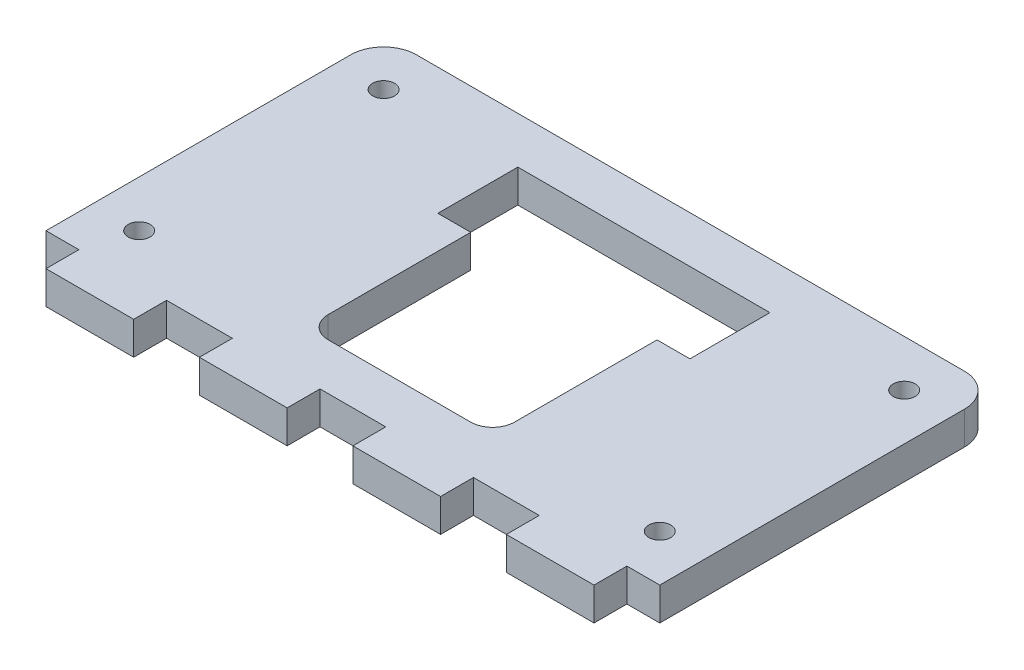
SolidWorks part; units mm, degrees
ref_plane "Plan de face" through (0, 0, 0) normal (0, 0, 1) x (1, 0, 0)
ref_plane "Plan de dessus" through (0, 0, 0) normal (0, 1, 0) x (1, 0, 0)
ref_plane "Plan de droite" through (0, 0, 0) normal (1, 0, 0) x (0, 0, -1)
sketch "Esquisse1" plane through (0, 0, 0) normal (0, 1, 0) x (1, 0, 0)
  line L0 (-28, -30.8) -> (-25, -30.8)
  line L1 (-25, 0) -> (25, 0)
  line L2 (-28, -3) -> (-28, -30.8)
  line L3 (-25, -33.8) -> (-17, -33.8)
  line L4 (28, -3) -> (28, -30.8)
  line L5 (-25, -30.8) -> (-25, -33.8)
  line L6 (-17, -33.8) -> (-17, -30.8)
  line L7 (-17, -30.8) -> (-11, -30.8)
  line L8 (-11, -30.8) -> (-11, -33.8)
  line L9 (-3, -33.8) -> (-3, -30.8)
  line L10 (-3, -30.8) -> (3, -30.8)
  line L11 (3, -30.8) -> (3, -33.8)
  line L12 (11, -33.8) -> (11, -30.8)
  line L13 (11, -30.8) -> (17, -30.8)
  line L14 (17, -30.8) -> (17, -33.8)
  line L15 (25, -33.8) -> (25, -30.8)
  line L16 (25, -30.8) -> (28, -30.8)
  line L17 (-11, -33.8) -> (-3, -33.8)
  line L18 (3, -33.8) -> (11, -33.8)
  line L19 (17, -33.8) -> (25, -33.8)
  line L20 (0, 0) -> (0, -30.8) construction
  line L21 (-11.5, -11.55) -> (-8.5, -11.55)
  line L22 (-23.75, -4.25) -> (23.75, -4.25) construction
  line L23 (-23.75, -4.25) -> (-23.75, -26.55) construction
  line L25 (23.75, -4.25) -> (23.75, -26.55) construction
  line L26 (-6.5, -26.55) -> (6.5, -26.55)
  line L27 (-11.5, -11.55) -> (-11.5, -4.25)
  line L28 (-11.5, -4.25) -> (11.5, -4.25)
  line L29 (11.5, -11.55) -> (11.5, -4.25)
  line L30 (-8.5, -11.55) -> (-8.5, -24.55)
  line L31 (11.5, -11.55) -> (8.5, -11.55)
  line L32 (8.5, -11.55) -> (8.5, -24.55)
  line L33 (-8.5, -26.55) -> (8.5, -26.55) construction
  line L34 (-23.75, -26.55) -> (23.75, -26.55) construction
  circle A0 centre (-23.75, -4.25) radius 1
  circle A1 centre (-23.75, -26.55) radius 1
  circle A2 centre (23.75, -26.55) radius 1
  circle A3 centre (23.75, -4.25) radius 1
  arc A4 (25, 0) -> (28, -3) centre (25, -3) cw
  arc A5 (-25, 0) -> (-28, -3) centre (-25, -3) ccw
  arc A6 (8.5, -24.55) -> (6.5, -26.55) centre (6.5, -24.55) cw
  arc A7 (-8.5, -24.55) -> (-6.5, -26.55) centre (-6.5, -24.55) ccw
  point P4 (0, -30.8)
  point P5 (0, -4.25)
  point P33 (0, -26.55)
  point P36 (28, 0)
  point P39 (-28, 0)
  point P40 (0, -4.25)
  dimension "D8" = 2
  dimension "D10" = 3
  dimension "D14" = 2
  dimension "D1" = 56
  dimension "D2" = 33.8
  dimension "D3" = 3
  dimension "D4" = 6
  dimension "D5" = 8
  dimension "D6" = 22.3
  dimension "D7" = 47.5
  dimension "D9" = 4.25
  dimension "D11" = 23
  dimension "D12" = 7.3
  dimension "D13" = 3
extrude "Boss.-Extru.1" add sketch "Esquisse1" along normal blind 3
